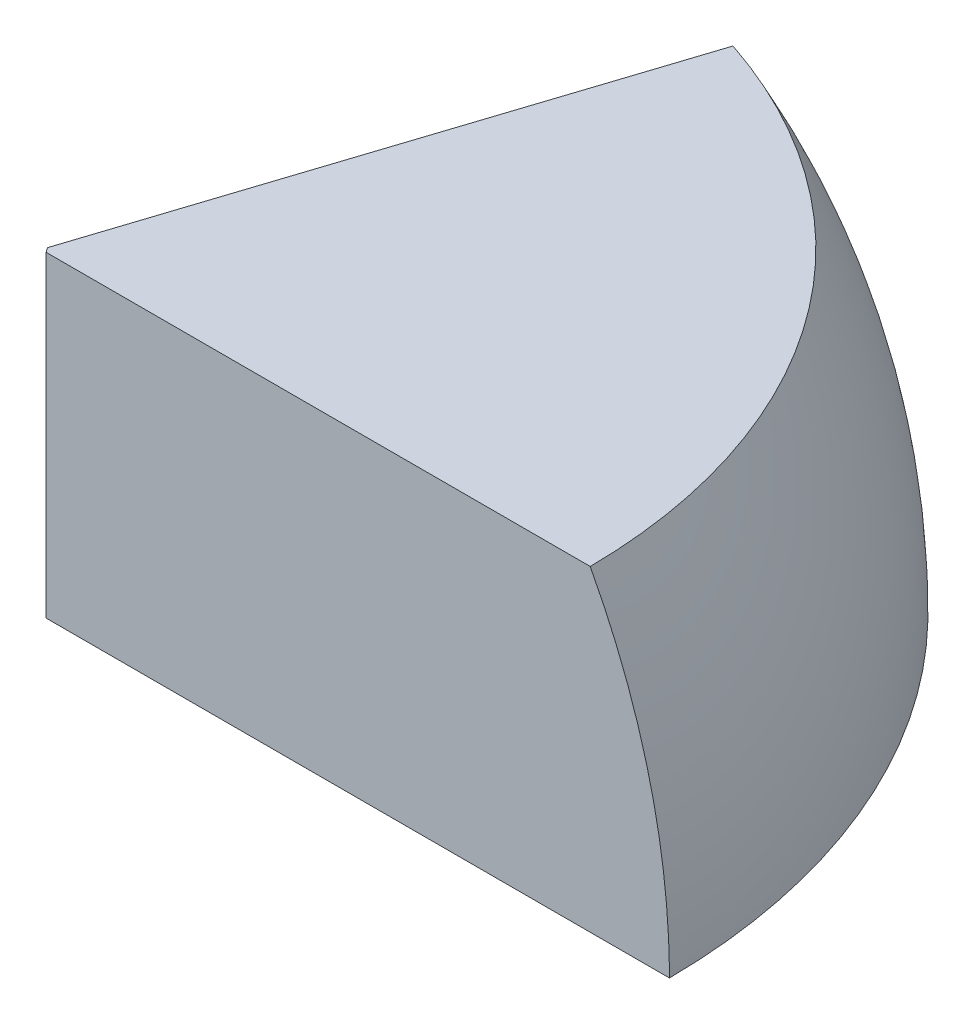
SolidWorks part; units mm, degrees
material "Polyurethane Foam Rigid"
ref_plane "Front Plane" through (0, 0, 0) normal (0, 0, 1) x (1, 0, 0)
ref_plane "Top Plane" through (0, 0, 0) normal (0, 1, 0) x (1, 0, 0)
ref_plane "Right Plane" through (0, 0, 0) normal (1, 0, 0) x (0, 0, -1)
sketch "Sketch1" plane through (0, 0, 0) normal (0, 0, 1) x (1, 0, 0)
  line L0 (0, 0) -> (0, 50.8)
  line L1 (0, 50.8) -> (88.9, 50.8)
  line L2 (0, 0) -> (101.6, 0)
  line L3 (101.6, 0) -> (101.6, -59.9199) construction
  arc A0 (88.9, 50.8) -> (101.6, 0) centre (-6.35, 0) cw
  dimension "D1" = 101.6
  dimension "D2" = 50.8
  dimension "D3" = 12.7
revolve "Revolve1" add sketch "Sketch1" angle 72 about L0
sketch "Sketch3" plane through (0, 0, 0) normal (-0.9511, 0, -0.309) x (-0.309, 0, 0.9511)
  line L7 (0, 50.8) -> (-88.9, 50.8)
  line L9 (-101.6, 0) -> (0, 0)
  line L10 (0, 0) -> (0, 50.8)
  line L13 (0, 50.8) -> (-88.9, 50.8)
  line L15 (-101.6, 0) -> (0, 0)
  line L16 (0, 0) -> (0, 50.8)
  arc A1 (-88.9, 50.8) -> (-101.6, 0) centre (6.35, 0) ccw
  arc A2 (-88.9, 50.8) -> (-101.6, 0) centre (6.35, 0) ccw
  dimension "D1" = 0
extrude "Cut-Extrude2" cut sketch "Sketch3" against normal blind 0.635
sketch "Sketch4" plane through (0, 0, 0) normal (0, 0, 1) x (1, 0, 0)
  line L6 (0.6677, 50.8) -> (0.6677, 0)
  line L7 (0.6677, 0) -> (101.6, 0)
  line L9 (88.9, 50.8) -> (0.6677, 50.8)
  line L12 (0.6677, 50.8) -> (0.6677, 0)
  line L13 (0.6677, 0) -> (101.6, 0)
  line L15 (88.9, 50.8) -> (0.6677, 50.8)
  arc A1 (101.6, 0) -> (88.9, 50.8) centre (-6.35, 0) ccw
  arc A2 (101.6, 0) -> (88.9, 50.8) centre (-6.35, 0) ccw
  dimension "D1" = 0
extrude "Cut-Extrude3" cut sketch "Sketch4" against normal blind 0.635
sketch "Sketch5" plane through (0, 50.8, 0) normal (0, 1, 0) x (1, 0, 0)
  line L0 (1.6589, 0.635) -> (0.874, 0.635)
  line L1 (88.8977, 0.635) -> (0.874, 0.635) construction
  line L2 (0.874, 0.635) -> (1.1166, 1.3815)
  line L3 (0.874, 0.635) -> (28.0748, 84.3505) construction
  line L4 (1.1166, 1.3815) -> (1.6589, 0.635)
  dimension "D1" = 0.635
extrude "Cut-Extrude4" cut sketch "Sketch5" against normal up to next
